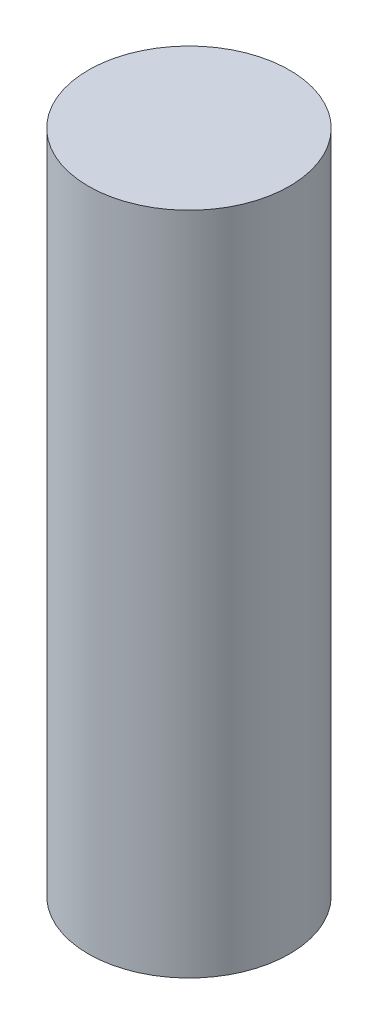
SolidWorks part; units mm, degrees
ref_plane "Front" through (0, 0, 0) normal (0, 0, 1) x (1, 0, 0)
ref_plane "Top" through (0, 0, 0) normal (0, 1, 0) x (1, 0, 0)
ref_plane "Right" through (0, 0, 0) normal (1, 0, 0) x (0, 0, -1)
sketch "Sketch1" plane through (0, 0, 0) normal (0, 1, 0) x (1, 0, 0)
  circle A0 centre (0, 0) radius 17.4
  dimension "D1" = 34.8
extrude "Boss-Extrude1" add sketch "Sketch1" along normal blind 115
